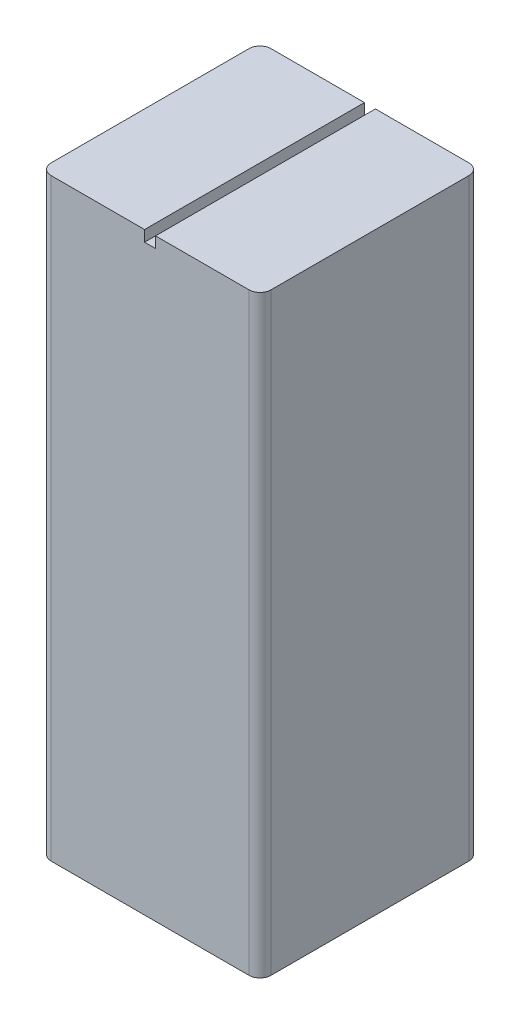
SolidWorks part; units mm, degrees
ref_plane "前视基准面" through (0, 0, 0) normal (0, 0, 1) x (1, 0, 0)
ref_plane "上视基准面" through (0, 0, 0) normal (0, 1, 0) x (1, 0, 0)
ref_plane "右视基准面" through (0, 0, 0) normal (1, 0, 0) x (0, 0, -1)
other "Configuration Table"
sketch "草图1" plane through (0, 0, 0) normal (0, 1, 0) x (1, 0, 0)
  line L1 (0, 0) -> (20, 0)
  line L2 (0, 0) -> (0, 20)
  line L3 (0, 20) -> (20, 20)
  line L4 (20, 0) -> (20, 20)
  line L5 (0, 0) -> (20, 20) construction
  line L6 (0, 20) -> (20, 0) construction
  point P4 (10, 10)
  dimension "D1" = 20
  dimension "D2" = 20
extrude "凸台-拉伸1" add sketch "草图1" along normal blind 54
fillet "圆角1" radius 1 4 edges at (20, 27, 0) (0, 27, 0) (20, 27, -20) (0, 27, -20)
sketch "草图2" plane through (0, 54, 0) normal (0, 1, 0) x (1, 0, 0)
  line L0 (19, 20) -> (1, 20) construction
  line L1 (9.5, 20) -> (10.5, 20)
  line L2 (9.5, 20) -> (9.5, 0)
  line L3 (9.5, 0) -> (10.5, 0)
  line L4 (10.5, 20) -> (10.5, 0)
  line L5 (9.5, 20) -> (10.5, 0) construction
  line L6 (9.5, 0) -> (10.5, 20) construction
  line L7 (10, 20) -> (10, 0) construction
  line L8 (1, 0) -> (19, 0) construction
  point P4 (10, 10)
  point P11 (0, 0)
  point P12 (0, 0)
  point P13 (10, 10.1048)
  dimension "D1" = 1
extrude "切除-拉伸1" cut sketch "草图2" against normal blind 1
